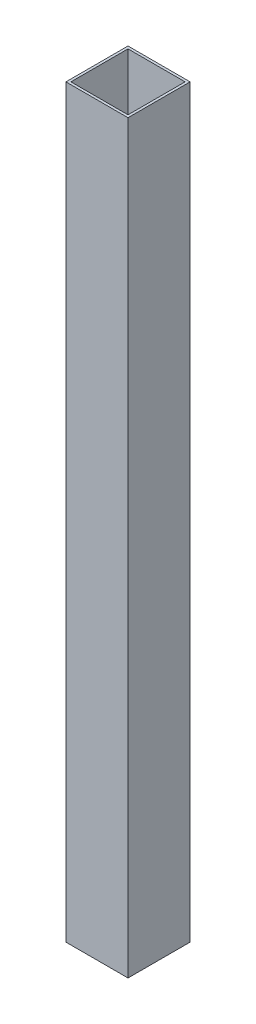
SolidWorks part; units mm, degrees
ref_plane "Front Plane" through (0, 0, 0) normal (0, 0, 1) x (1, 0, 0)
ref_plane "Top Plane" through (0, 0, 0) normal (0, 1, 0) x (1, 0, 0)
ref_plane "Right Plane" through (0, 0, 0) normal (1, 0, 0) x (0, 0, -1)
sketch "Sketch1" plane through (0, 0, 0) normal (0, 1, 0) x (1, 0, 0)
  line L0 (-23, 23) -> (23, 23)
  line L1 (-25, -25) -> (25, -25)
  line L2 (-25, -25) -> (-25, 25)
  line L3 (-25, 25) -> (25, 25)
  line L4 (25, -25) -> (25, 25)
  line L5 (-25, -25) -> (25, 25) construction
  line L6 (-25, 25) -> (25, -25) construction
  line L7 (23, -23) -> (23, 23)
  line L8 (-23, -23) -> (23, -23)
  line L9 (-23, -23) -> (-23, 23)
  point P0 (0, 0)
  dimension "D1" = 50
  dimension "D2" = 2
extrude "Boss-Extrude1" add sketch "Sketch1" along normal blind 600
